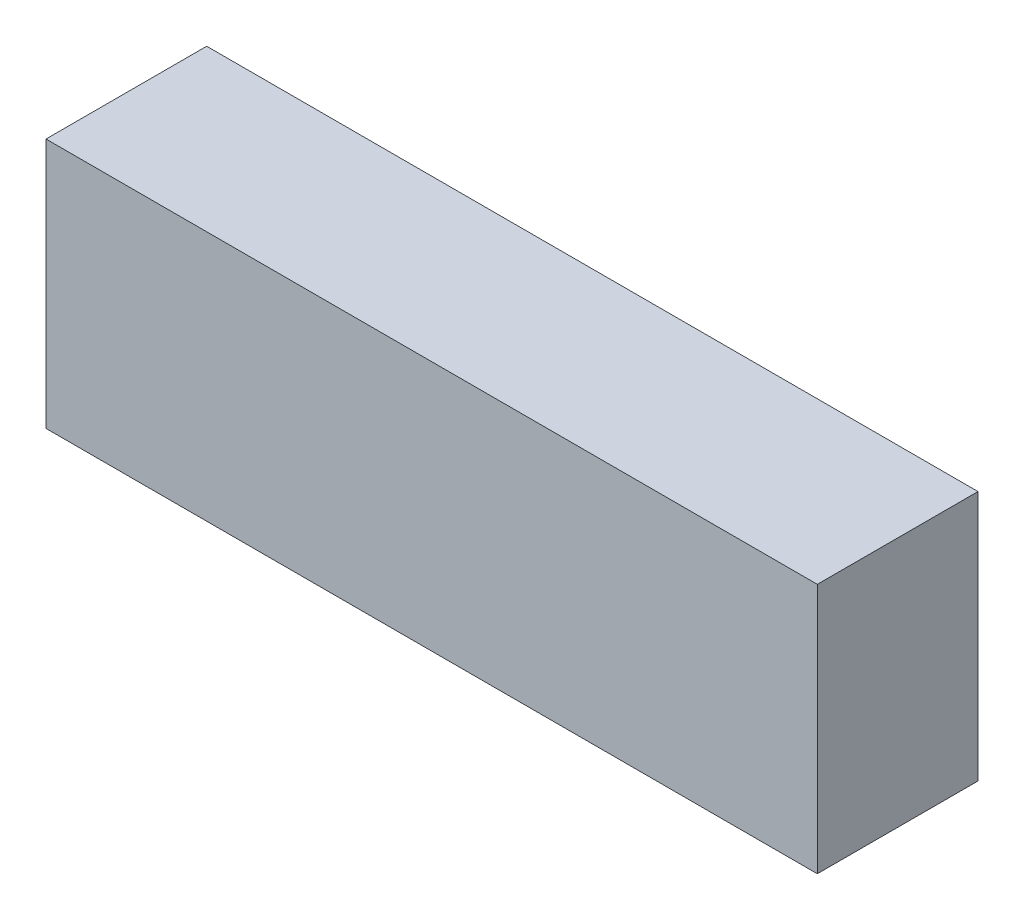
SolidWorks part; units mm, degrees
ref_plane "Front Plane" through (0, 0, 0) normal (0, 0, 1) x (1, 0, 0)
ref_plane "Top Plane" through (0, 0, 0) normal (0, 1, 0) x (1, 0, 0)
ref_plane "Right Plane" through (0, 0, 0) normal (1, 0, 0) x (0, 0, -1)
sketch "Sketch1" plane through (0, 0, 0) normal (0, 1, 0) x (1, 0, 0)
  line L1 (-60, -12.5) -> (60, -12.5)
  line L2 (-60, -12.5) -> (-60, 12.5)
  line L3 (-60, 12.5) -> (60, 12.5)
  line L4 (60, -12.5) -> (60, 12.5)
extrude "Boss-Extrude1" add sketch "Sketch1" along normal blind 39
